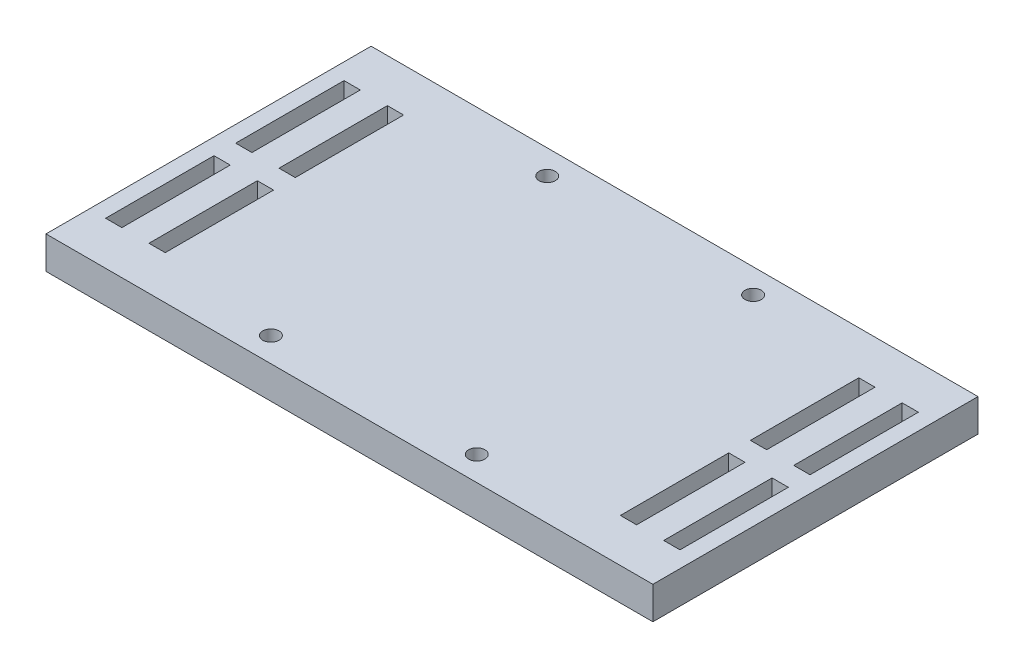
SolidWorks part; units mm, degrees
ref_plane "前视基准面" through (0, 0, 0) normal (0, 0, 1) x (1, 0, 0)
ref_plane "上视基准面" through (0, 0, 0) normal (0, 1, 0) x (1, 0, 0)
ref_plane "右视基准面" through (0, 0, 0) normal (1, 0, 0) x (0, 0, -1)
other "Configuration Table"
sketch "草图1" plane through (0, 0, 0) normal (0, 1, 0) x (1, 0, 0)
  line L0 (56, 0) -> (56, -60)
  line L1 (0, 0) -> (112, 0)
  line L2 (0, 0) -> (0, -60)
  line L3 (0, -60) -> (112, -60)
  line L4 (112, 0) -> (112, -60)
  line L5 (3, -8) -> (6, -8)
  line L6 (3, -8) -> (3, -28)
  line L7 (3, -28) -> (6, -28)
  line L8 (6, -8) -> (6, -28)
  line L9 (0, -30) -> (107.5621, -30)
  line L10 (3, -32) -> (6, -32)
  line L11 (6, -52) -> (6, -32)
  line L12 (3, -52) -> (6, -52)
  line L13 (3, -52) -> (3, -32)
  line L14 (109, -28) -> (106, -28)
  line L15 (106, -8) -> (106, -28)
  line L16 (109, -8) -> (106, -8)
  line L17 (109, -8) -> (109, -28)
  line L18 (109, -52) -> (109, -32)
  line L19 (109, -52) -> (106, -52)
  line L20 (106, -52) -> (106, -32)
  line L21 (109, -32) -> (106, -32)
  line L22 (11, -32) -> (14, -32)
  line L23 (11, -8) -> (14, -8)
  line L24 (11, -8) -> (11, -28)
  line L25 (11, -28) -> (14, -28)
  line L26 (14, -8) -> (14, -28)
  line L27 (14, -52) -> (14, -32)
  line L28 (11, -52) -> (14, -52)
  line L29 (11, -52) -> (11, -32)
  line L30 (101, -28) -> (98, -28)
  line L31 (98, -8) -> (98, -28)
  line L32 (101, -8) -> (98, -8)
  line L33 (101, -8) -> (101, -28)
  line L34 (101, -52) -> (101, -32)
  line L35 (101, -52) -> (98, -52)
  line L36 (98, -52) -> (98, -32)
  line L37 (101, -32) -> (98, -32)
  circle A0 centre (75, -4.5) radius 1.5
  circle A1 centre (37, -4.5) radius 1.5
  circle A2 centre (75, -55.5) radius 1.5
  circle A3 centre (37, -55.5) radius 1.5
  dimension "D10" = 3
  dimension "D11" = 19
  dimension "D12" = 25.5
  dimension "D1" = 112
  dimension "D2" = 60
  dimension "D3" = 3
  dimension "D4" = 3
  dimension "D5" = 20
  dimension "D6" = 8
  dimension "D7" = 3
  dimension "D8" = 20
  dimension "D9" = 5
extrude "凸台-拉伸1" add sketch "草图1" along normal blind 6 contours L2 L9 L0 L1 L5 L8 L7 L6 | L9 L2 L3 L0 L12 L13 L10 L11 | L0 L9 L4 L1 L16 L17 L14 L15 | L9 L0 L3 L4 L21 L18 L19 L20
